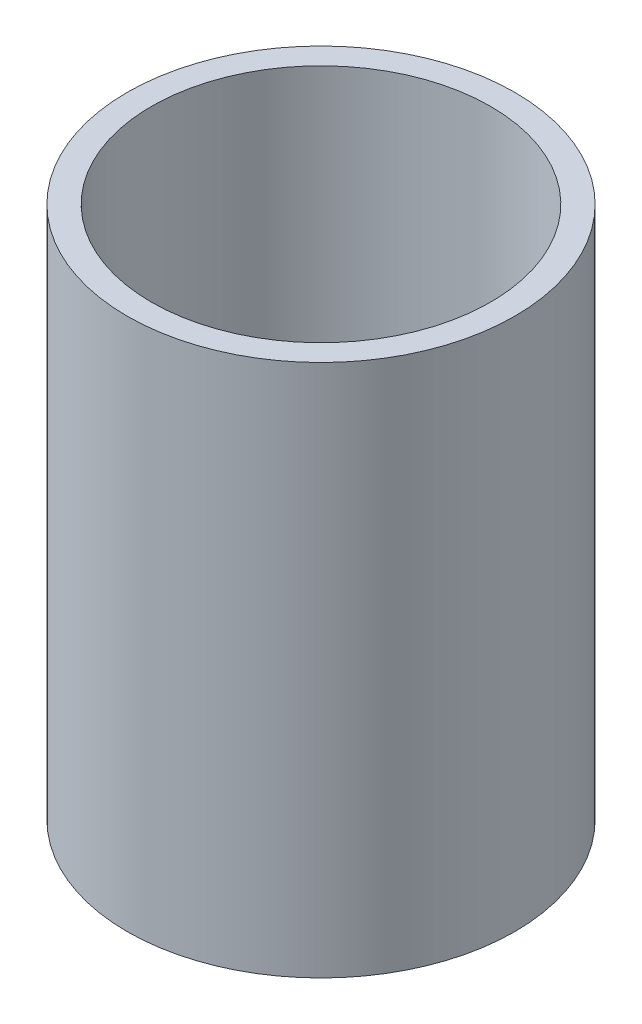
SolidWorks part; units mm, degrees
ref_plane "Front Plane" through (0, 0, 0) normal (0, 0, 1) x (1, 0, 0)
ref_plane "Top Plane" through (0, 0, 0) normal (0, 1, 0) x (1, 0, 0)
ref_plane "Right Plane" through (0, 0, 0) normal (1, 0, 0) x (0, 0, -1)
sketch "Sketch1" plane through (0, 0, 0) normal (0, 1, 0) x (1, 0, 0)
  circle A0 centre (0, 0) radius 40
  circle A1 centre (0, 0) radius 35
  dimension "D1" = 70
  dimension "D2" = 80
extrude "Boss-Extrude1" add sketch "Sketch1" along normal mid plane 110
